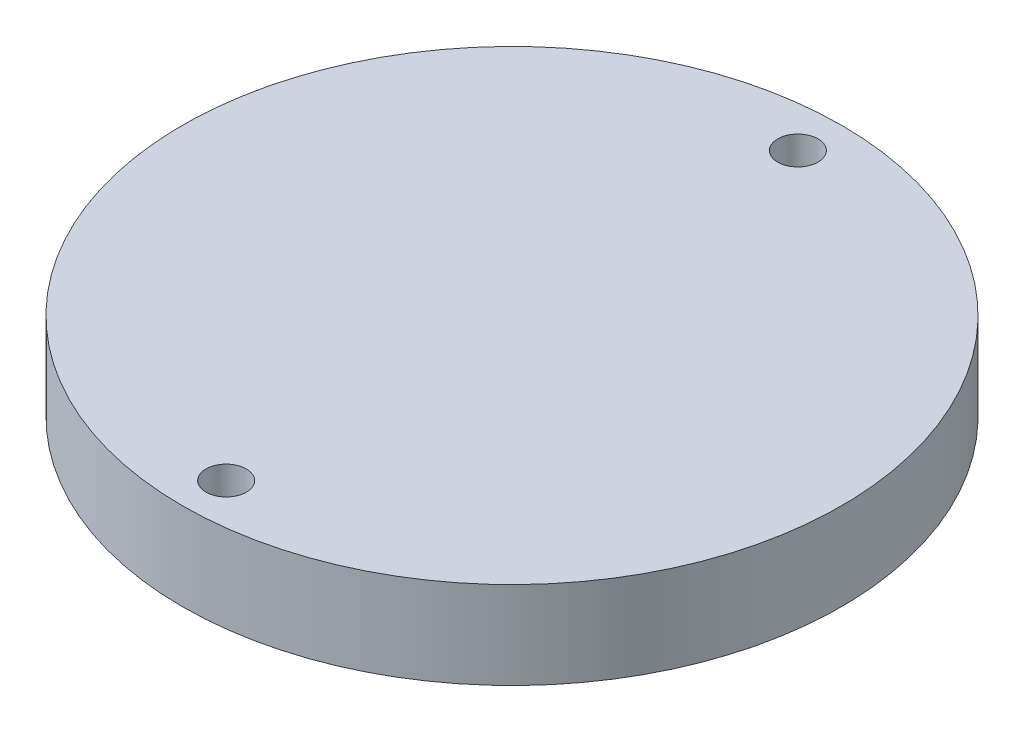
SolidWorks part; units mm, degrees
ref_plane "Front Plane" through (0, 0, 0) normal (0, 0, 1) x (1, 0, 0)
ref_plane "Top Plane" through (0, 0, 0) normal (0, 1, 0) x (1, 0, 0)
ref_plane "Right Plane" through (0, 0, 0) normal (1, 0, 0) x (0, 0, -1)
sketch "Sketch1" plane through (0, 0, 0) normal (0, 1, 0) x (1, 0, 0)
  circle A0 centre (0, 0) radius 18.5
  circle A1 centre (0, 0) radius 24.5
  dimension "D1" = 37
  dimension "D2" = 6
extrude "Boss-Extrude1" add sketch "Sketch1" along normal blind 4.5
sketch "Sketch2" plane through (0, 4.5, 0) normal (0, 1, 0) x (1, 0, 0)
  circle A1 centre (0, 0) radius 24.5
  circle A2 centre (0, 0) radius 24.5
  dimension "D1" = 0
extrude "Boss-Extrude2" add sketch "Sketch2" along normal blind 2
sketch "Sketch3" plane through (0, 0, 0) normal (0, -1, 0) x (1, 0, 0)
  circle A0 centre (0, -21.25) radius 1.5
  circle A1 centre (0, 0) radius 21.25 construction
  circle A2 centre (0, 21.25) radius 1.5
  dimension "D1" = 3
  dimension "D2" = 42.5
  dimension "D3" = 3
extrude "Cut-Extrude1" cut sketch "Sketch3" against normal through all
